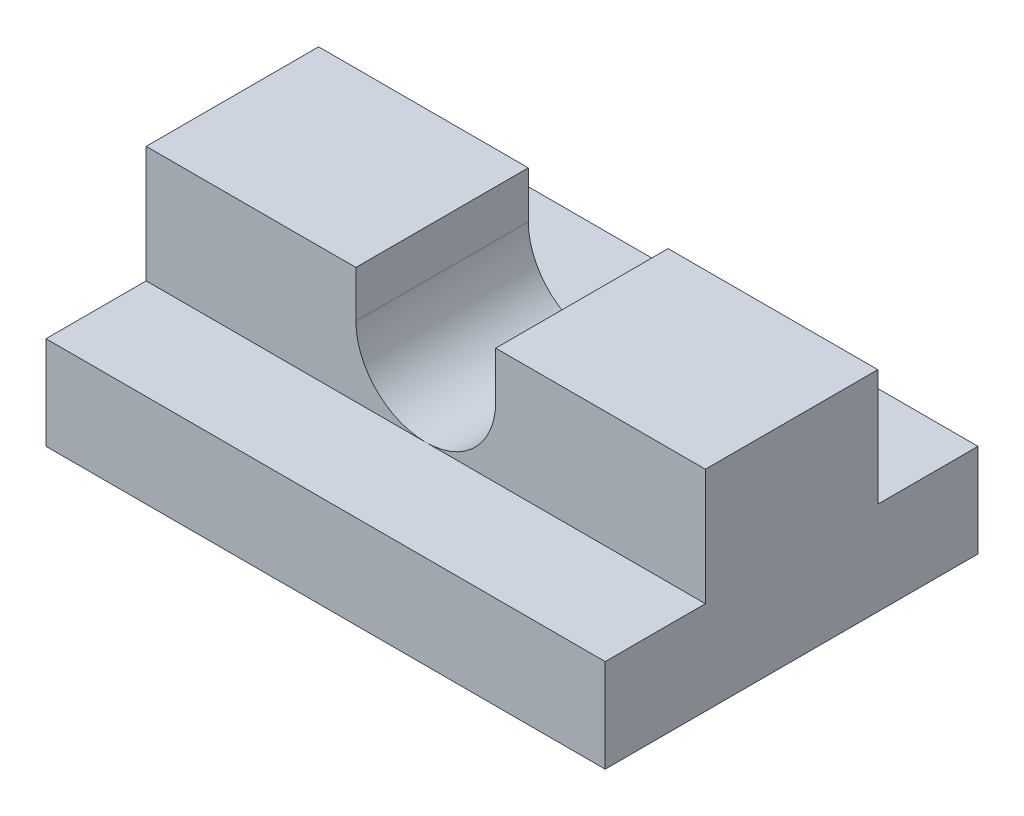
SolidWorks part; units mm, degrees
ref_plane "Front Plane" through (0, 0, 0) normal (0, 0, 1) x (1, 0, 0)
ref_plane "Top Plane" through (0, 0, 0) normal (0, 1, 0) x (1, 0, 0)
ref_plane "Right Plane" through (0, 0, 0) normal (1, 0, 0) x (0, 0, -1)
sketch "Sketch1" plane through (0, 0, 0) normal (0, 1, 0) x (1, 0, 0)
  line L1 (0, -4) -> (12, -4)
  line L2 (0, -4) -> (0, 4)
  line L3 (0, 4) -> (12, 4)
  line L4 (12, -4) -> (12, 4)
  point P4 (0, 0)
  dimension "D1" = 8
  dimension "D2" = 12
extrude "Boss-Extrude1" add sketch "Sketch1" along normal blind 2
sketch "Sketch2" plane through (0, 2, 0) normal (0, 1, 0) x (1, 0, 0)
  line L0 (12, -4) -> (12, 4) construction
  line L1 (0, -1.85) -> (12, -1.85)
  line L2 (0, -1.85) -> (0, 1.85)
  line L3 (0, 1.85) -> (12, 1.85)
  line L4 (12, -1.85) -> (12, 1.85)
  point P4 (0, 0)
  dimension "D1" = 3.7
extrude "Boss-Extrude2" add sketch "Sketch2" along normal blind 2.5
sketch "Sketch3" plane through (0, 0, 1.85) normal (0, 0, 1) x (1, 0, 0)
  line L0 (0, 4.5) -> (0, 2) construction
  line L2 (0, 2) -> (12, 2) construction
  line L3 (4.5, 3.5) -> (4.5, 5)
  line L4 (4.5, 5) -> (7.5, 5)
  line L5 (7.5, 5) -> (7.5, 3.5)
  arc A0 (4.5, 3.5) -> (7.5, 3.5) centre (6, 3.5) ccw
  dimension "D1" = 3
  dimension "D2" = 6
extrude "Cut-Extrude1" cut sketch "Sketch3" against normal through all
